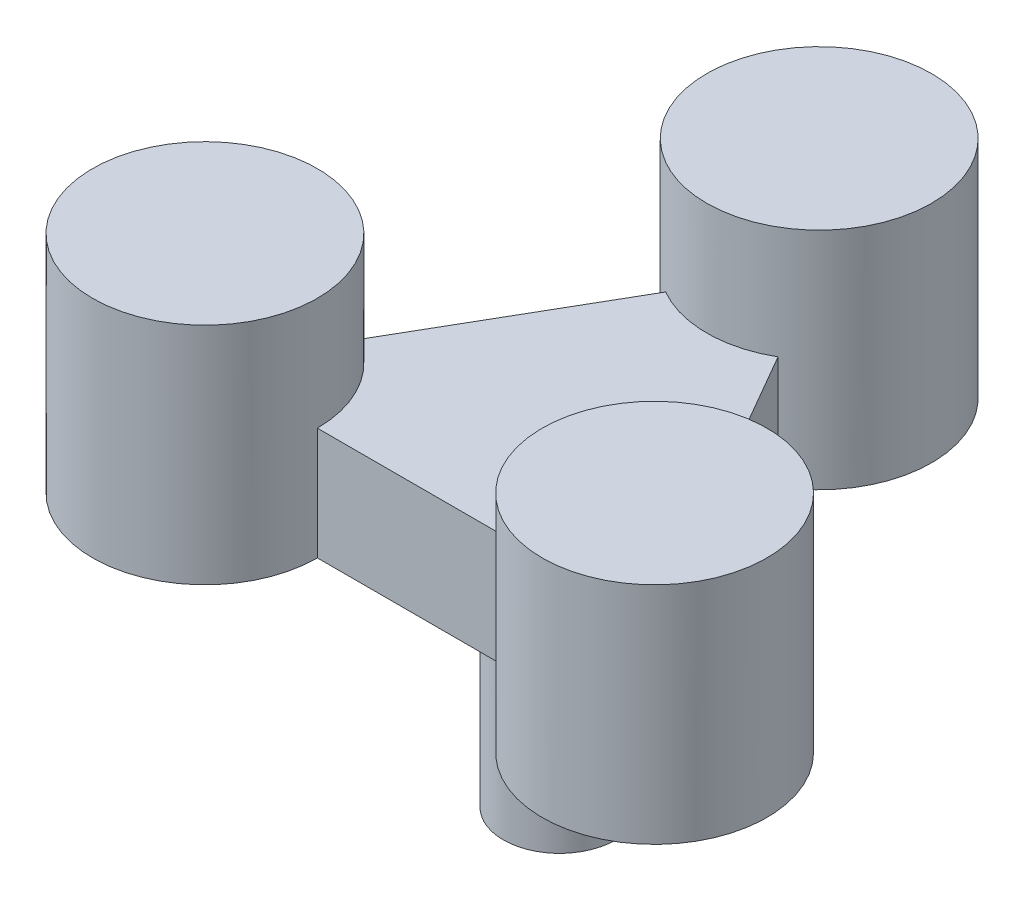
SolidWorks part; units mm, degrees
ref_plane "Front Plane" through (0, 0, 0) normal (0, 0, 1) x (1, 0, 0)
ref_plane "Top Plane" through (0, 0, 0) normal (0, 1, 0) x (1, 0, 0)
ref_plane "Right Plane" through (0, 0, 0) normal (1, 0, 0) x (0, 0, -1)
sketch "Sketch1" plane through (0, 0, 0) normal (0, 1, 0) x (1, 0, 0)
  line L0 (-6.35, 18.3309) -> (-19.05, -3.6662)
  line L1 (-12.7, -14.6647) -> (12.7, -14.6647)
  line L2 (19.05, -3.6662) -> (6.35, 18.3309)
  line L3 (0, 29.3294) -> (0, 0) construction
  line L4 (0, 0) -> (-25.4, -14.6647) construction
  line L5 (0, 0) -> (25.4, -14.6647) construction
  arc A0 (-19.05, -3.6662) -> (-12.7, -14.6647) centre (-25.4, -14.6647) ccw
  arc A1 (12.7, -14.6647) -> (19.05, -3.6662) centre (25.4, -14.6647) ccw
  arc A2 (6.35, 18.3309) -> (-6.35, 18.3309) centre (0, 29.3294) ccw
  dimension "D4" = 25.4
  dimension "D5" = 25.4
  dimension "D6" = 25.4
  dimension "D1" = 60
  dimension "D2" = 60
  dimension "D3" = 50.8
extrude "Boss-Extrude1" add sketch "Sketch1" along normal blind 12.7
sketch "Sketch2" plane through (0, 12.7, 0) normal (0, 1, 0) x (1, 0, 0)
  circle A0 centre (-25.4, -14.6647) radius 12.7
  circle A1 centre (25.4, -14.6647) radius 12.7
  circle A2 centre (0, 29.3294) radius 12.7
extrude "Boss-Extrude2" add sketch "Sketch2" along normal blind 12.7
sketch "Sketch3" plane through (0, 0, 0) normal (0, -1, 0) x (-1, 0, 0)
  circle A0 centre (0, 0) radius 6.35
  dimension "D1" = 12.7
extrude "Boss-Extrude3" add sketch "Sketch3" along normal blind 25.4
